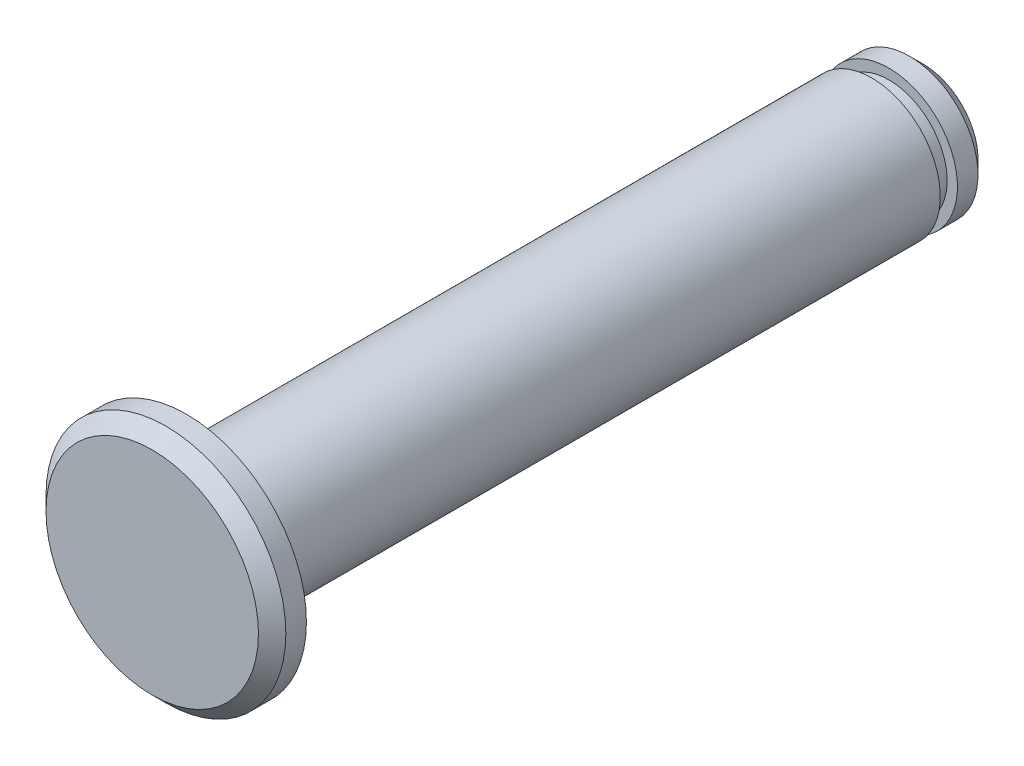
SolidWorks part; units mm, degrees
material "AISI 1020"
ref_plane "Front Plane" through (0, 0, 0) normal (0, 0, 1) x (1, 0, 0)
ref_plane "Top Plane" through (0, 0, 0) normal (0, 1, 0) x (1, 0, 0)
ref_plane "Right Plane" through (0, 0, 0) normal (1, 0, 0) x (0, 0, -1)
sketch "Sketch1" plane through (0, 0, 0) normal (0, 1, 0) x (1, 0, 0)
  line L0 (0, 59.9245) -> (0, -42.0284) construction
  line L1 (0, -9.1034) -> (-7, -9.1034)
  line L2 (-7, -9.1034) -> (-7, -7.1034)
  line L3 (-7, -7.1034) -> (-4, -7.1034)
  line L4 (-4, -7.1034) -> (-4, 32.8966)
  line L5 (-4, 32.8966) -> (-3.4, 32.8966)
  line L6 (-3.4, 32.8966) -> (-3.4, 33.8966)
  line L7 (-3.4, 33.8966) -> (-4, 33.8966)
  line L8 (-4, 33.8966) -> (-4, 35.8966)
  line L9 (0, -9.1034) -> (0, 35.8966)
  line L10 (0, 35.8966) -> (-4, 35.8966)
  dimension "D1" = 8
  dimension "D2" = 0.6
  dimension "D3" = 3
  dimension "D4" = 2
  dimension "D5" = 40
  dimension "D6" = 1
  dimension "D7" = 2
revolve "Revolve1" add sketch "Sketch1" angle 360 about L0
chamfer "Chamfer1" distance 0.8 angle 45 2 edges at (-4, 0, -35.8966) (-7, 0, 9.1034)
